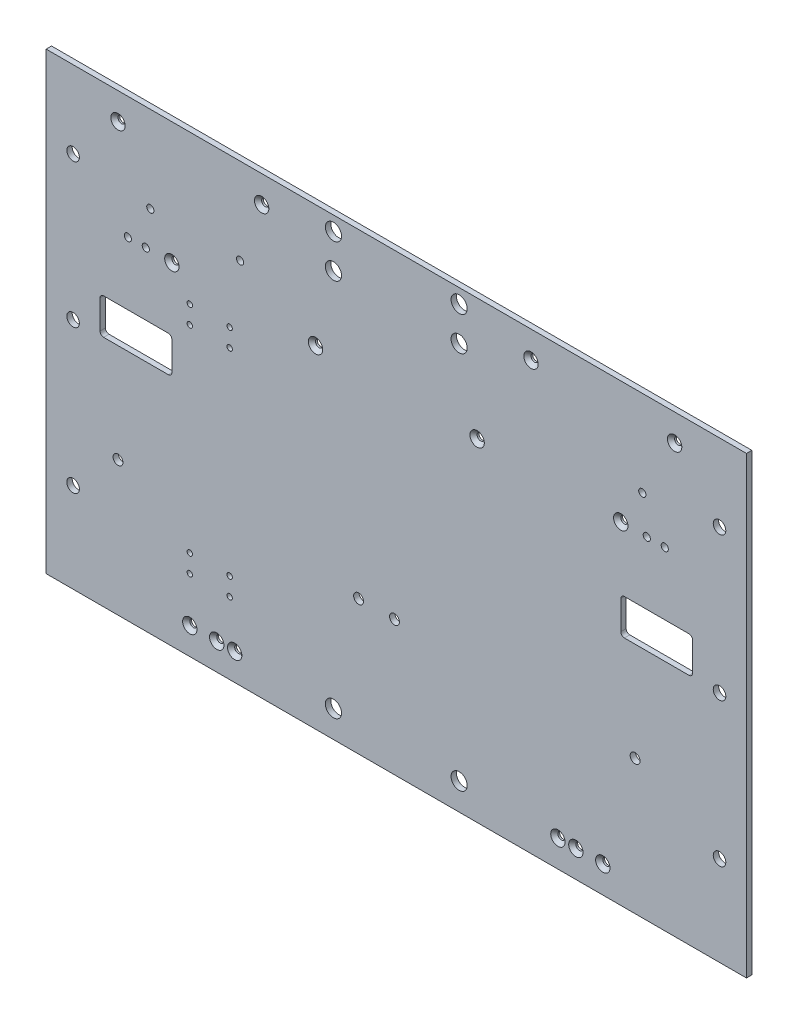
SolidWorks part; units mm, degrees
material "1060 合金"
ref_plane "前视基准面" through (0, 0, 0) normal (0, 0, 1) x (1, 0, 0)
ref_plane "上视基准面" through (0, 0, 0) normal (0, 1, 0) x (1, 0, 0)
ref_plane "右视基准面" through (0, 0, 0) normal (1, 0, 0) x (0, 0, -1)
sketch "草图1" plane through (0, 0, 0) normal (0, 0, 1) x (1, 0, 0)
  line L1 (-195, 126.5) -> (195, 126.5)
  line L2 (-195, 126.5) -> (-195, -126.5)
  line L3 (-195, -126.5) -> (195, -126.5)
  line L4 (195, 126.5) -> (195, -126.5)
  point P4 (0, 126.5)
  point P6 (195, 0)
  dimension "D1" = 390
  dimension "D2" = 253
extrude "凸台-拉伸1" add sketch "草图1" along normal blind 3
sketch "草图3" plane through (0, 0, 0) normal (0, 0, 1) x (1, 0, 0)
  line L0 (0, 126.5) -> (0, -126.5) construction
  line L1 (195, 126.5) -> (-195, 126.5) construction
  line L2 (-195, -126.5) -> (195, -126.5) construction
  line L3 (-195, -96.5) -> (195, -96.5) construction
  line L4 (-195, 126.5) -> (-195, -126.5) construction
  line L5 (195, -126.5) -> (195, 126.5) construction
  circle A0 centre (-35, -111.5) radius 4.5
  circle A1 centre (35, -111.5) radius 4.5
  circle A2 centre (-180, -76.5) radius 3.5
  circle A3 centre (180, -76.5) radius 3.5
  circle A4 centre (-35, 118.5) radius 4.5
  circle A5 centre (35, 118.5) radius 4.5
  circle A6 centre (-35, 99.5) radius 4.5
  circle A7 centre (35, 99.5) radius 4.5
  circle A8 centre (-155, -51.5) radius 2.75
  circle A9 centre (-21, -51.5) radius 2.75
  circle A10 centre (-1, -51.5) radius 2.75
  circle A11 centre (133, -51.5) radius 2.75
  circle A12 centre (-149.5, 58.5) radius 2
  circle A13 centre (-139.5, 58.5) radius 2
  circle A14 centre (139.5, 58.5) radius 2
  circle A15 centre (149.5, 58.5) radius 2
  circle A16 centre (-137, 78.5) radius 2
  circle A18 centre (-87, 78.5) radius 2
  circle A19 centre (-180, 3.5) radius 3.5
  circle A20 centre (-180, 83.5) radius 3.5
  circle A21 centre (180, 83.5) radius 3.5
  circle A22 centre (180, 3.5) radius 3.5
  circle A23 centre (-155, 111.5) radius 2
  circle A24 centre (-75, 111.5) radius 2
  circle A25 centre (-45, 58.5) radius 2
  circle A26 centre (-125, 58.5) radius 2
  circle A27 centre (45, 58.5) radius 2
  circle A28 centre (137, 78.5) radius 2
  circle A29 centre (75, 111.5) radius 2
  circle A30 centre (155, 111.5) radius 2
  circle A31 centre (-115, -111.5) radius 2
  circle A32 centre (115, -111.5) radius 2
  circle A33 centre (125, 58.5) radius 2
  circle A34 centre (-100, -111.5) radius 2
  circle A35 centre (-90, -111.5) radius 2
  circle A36 centre (90, -111.5) radius 2
  circle A37 centre (100, -111.5) radius 2
  circle A38 centre (-115, 33.5) radius 1.5
  circle A39 centre (-92.8, 43.5) radius 1.5
  circle A40 centre (-115, 43.5) radius 1.5
  circle A41 centre (-92.8, 33.5) radius 1.5
  circle A42 centre (-115, -86.5) radius 1.5
  circle A43 centre (-92.8, -76.5) radius 1.5
  circle A44 centre (-115, -76.5) radius 1.5
  circle A45 centre (-92.8, -86.5) radius 1.5
  point P102 (0, 0)
  point P103 (0, 0)
  dimension "D2" = 9
  dimension "D5" = 7
  dimension "D8" = 9
  dimension "D12" = 5.5
  dimension "D20" = 4
  dimension "D24" = 4
  dimension "D33" = 4
  dimension "D35" = 4
  dimension "D40" = 3
  dimension "D47" = 3
  dimension "D1" = 30
  dimension "D3" = 70
  dimension "D4" = 15
  dimension "D6" = 50
  dimension "D7" = 360
  dimension "D9" = 8
  dimension "D10" = 70
  dimension "D11" = 27
  dimension "D13" = 40
  dimension "D14" = 75
  dimension "D15" = 134
  dimension "D16" = 20
  dimension "D17" = 134
  dimension "D18" = 68
  dimension "D19" = 45.5
  dimension "D21" = 10
  dimension "D22" = 48
  dimension "D23" = 50
  dimension "D25" = 58
  dimension "D26" = 80
  dimension "D27" = 80
  dimension "D28" = 15
  dimension "D29" = 53
  dimension "D30" = 40
  dimension "D31" = 70
  dimension "D32" = 80
  dimension "D34" = 80
  dimension "D36" = 15
  dimension "D37" = 80
  dimension "D38" = 10
  dimension "D39" = 90
  dimension "D41" = 10
  dimension "D42" = 22.2
  dimension "D43" = 80
  dimension "D44" = 10
  dimension "D45" = 22.2
  dimension "D46" = 40
  dimension "D48" = 120
extrude "切除-拉伸3" cut sketch "草图3" along normal through all
sketch "草图5" plane through (0, 0, 0) normal (0, 0, 1) x (1, 0, 0)
  line L0 (0, 126.5) -> (0, -126.5) construction
  line L1 (-165, 23.5) -> (-125, 23.5)
  line L2 (-165, 23.5) -> (-165, 3.5)
  line L3 (-165, 3.5) -> (-125, 3.5)
  line L4 (-125, 23.5) -> (-125, 3.5)
  line L5 (195, 126.5) -> (-195, 126.5) construction
  line L6 (-195, -126.5) -> (195, -126.5) construction
  line L7 (-195, 126.5) -> (-195, -126.5) construction
  line L8 (125, 23.5) -> (125, 3.5)
  line L9 (165, 3.5) -> (125, 3.5)
  line L10 (165, 23.5) -> (165, 3.5)
  line L11 (165, 23.5) -> (125, 23.5)
  dimension "D1" = 20
  dimension "D2" = 40
  dimension "D3" = 30
  dimension "D4" = 130
extrude "切除-拉伸4" cut sketch "草图5" along normal through all
fillet "圆角1" radius 2 8 edges at (125, 23.5, 1.5) (165, 23.5, 1.5) (165, 3.5, 1.5) (125, 3.5, 1.5) (-165, 3.5, 1.5) (-125, 3.5, 1.5) (-125, 23.5, 1.5) (-165, 23.5, 1.5)
chamfer "倒角1" distance 2 angle 45 14 edges at (113, -111.5, 3) (-113, -111.5, 3) (43, 58.5, 3) (153, 111.5, 3) (73, 111.5, 3) (-43, 58.5, 3) (-73, 111.5, 3) (-153, 111.5, 3) (-123, 58.5, 3) (123, 58.5, 3) (98, -111.5, 3) (88, -111.5, 3) (-88, -111.5, 3) (-98, -111.5, 3)
